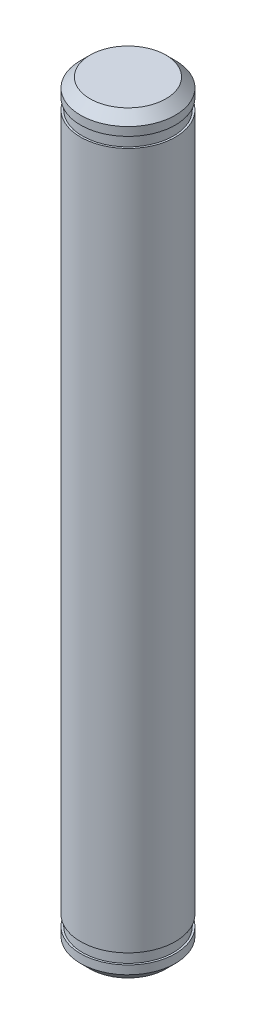
SolidWorks part; units mm, degrees
ref_plane "前视基准面" through (0, 0, 0) normal (0, 0, 1) x (1, 0, 0)
ref_plane "上视基准面" through (0, 0, 0) normal (0, 1, 0) x (1, 0, 0)
ref_plane "右视基准面" through (0, 0, 0) normal (1, 0, 0) x (0, 0, -1)
other "Configuration Table"
sketch "草图1" plane through (0, 0, 0) normal (0, 0, 1) x (1, 0, 0)
  line L0 (0, 61.8249) -> (0, -44.5084) construction
  line L1 (0, 39.745) -> (5, 39.745)
  line L2 (5, 39.745) -> (5, 29.0012)
  line L6 (5, -29.0012) -> (5, -39.745)
  line L7 (5, -39.745) -> (0, -39.745)
  line L8 (0, 0) -> (41.6667, 0) construction
  line L9 (0, 39.745) -> (0, -39.745)
  line L10 (5, 29.0012) -> (5, -29.0012)
  dimension "D1" = 5
  dimension "D2" = 5
  dimension "D5" = 79.49
revolve "旋转1" add sketch "草图1" angle 360 about L9
chamfer "倒角1" distance 1 angle 45 2 edges at (0, -39.745, 5) (0, 39.745, 5)
ref_plane "基准面1" through (0, 0, 0) normal (0, 1, 0) x (1, 0, 0)
sketch "草图2" plane through (0, 39.745, 0) normal (0, 1, 0) x (1, 0, 0)
  circle A0 centre (0, 0) radius 5 construction
  circle A1 centre (0, 0) radius 5
  circle A2 centre (0, 0) radius 4.8
  dimension "D1" = 9.6
extrude "切除-拉伸1" cut sketch "草图2" along normal blind 1.1 from offset 3 offset against normal yes
mirror "镜向1" about plane through (0, 0, 0) normal (0, 1, 0) of "切除-拉伸1"
